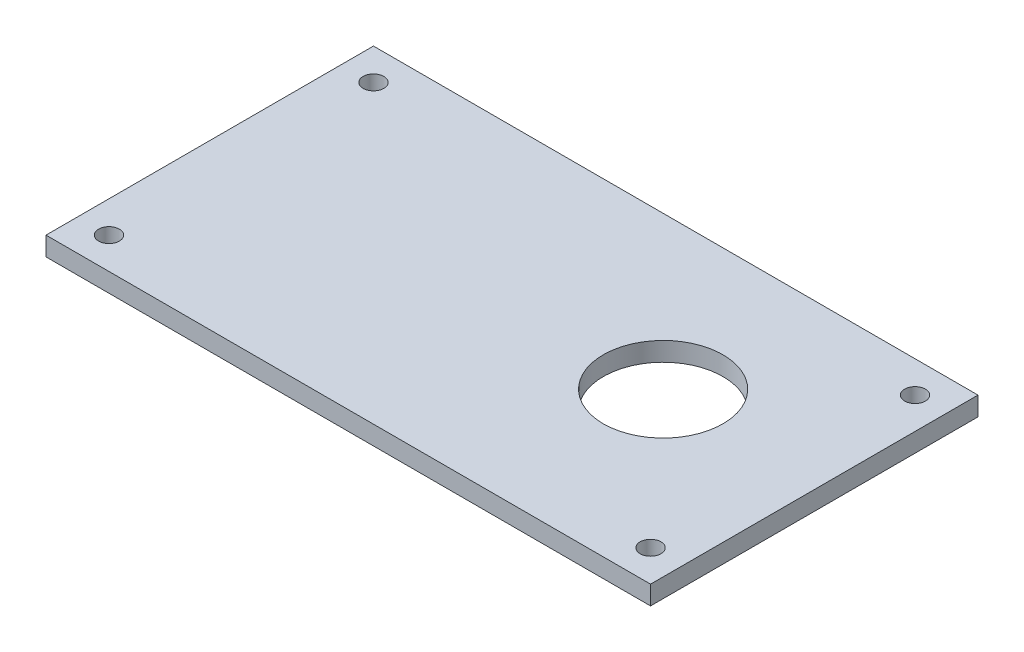
SolidWorks part; units mm, degrees
ref_plane "Front Plane" through (0, 0, 0) normal (0, 0, 1) x (1, 0, 0)
ref_plane "Top Plane" through (0, 0, 0) normal (0, 1, 0) x (1, 0, 0)
ref_plane "Right Plane" through (0, 0, 0) normal (1, 0, 0) x (0, 0, -1)
sketch "Sketch1" plane through (0, 0, 0) normal (0, 1, 0) x (1, 0, 0)
  line L0 (-52.8, 0) -> (52.8, 0) construction
  line L1 (-48, 26) -> (48, 26)
  line L2 (-48, 26) -> (-48, -26)
  line L3 (-48, -26) -> (48, -26)
  line L4 (48, 26) -> (48, -26)
  line L5 (0, -31.7498) -> (0, 31.7498) construction
  dimension "D1" = 96
  dimension "D2" = 52
  dimension "D3" = 26
  dimension "D4" = 48
extrude "Boss-Extrude1" add sketch "Sketch1" along normal blind 3
sketch "Sketch2" plane through (0, 3, 0) normal (0, 1, 0) x (1, 0, 0)
  line L0 (48, 26) -> (-48, 26) construction
  line L1 (-48, 26) -> (-48, -26) construction
  line L3 (48, -26) -> (48, 26) construction
  circle A0 centre (-43, 21) radius 1.65
  circle A1 centre (43, 21) radius 1.65
  circle A2 centre (43, -21) radius 1.65
  circle A3 centre (-43, -21) radius 1.65
  circle A4 centre (22.2, 1.8) radius 9.5
  point P18 (23.794, 26)
  dimension "D3" = 3.3
  dimension "D6" = 19
  dimension "D7" = 25.8
  dimension "D1" = 5
  dimension "D2" = 5
  dimension "D8" = 24.2
  dimension "D4" = 2
  dimension "D5" = 2
extrude "Cut-Extrude1" cut sketch "Sketch2" against normal blind 3
